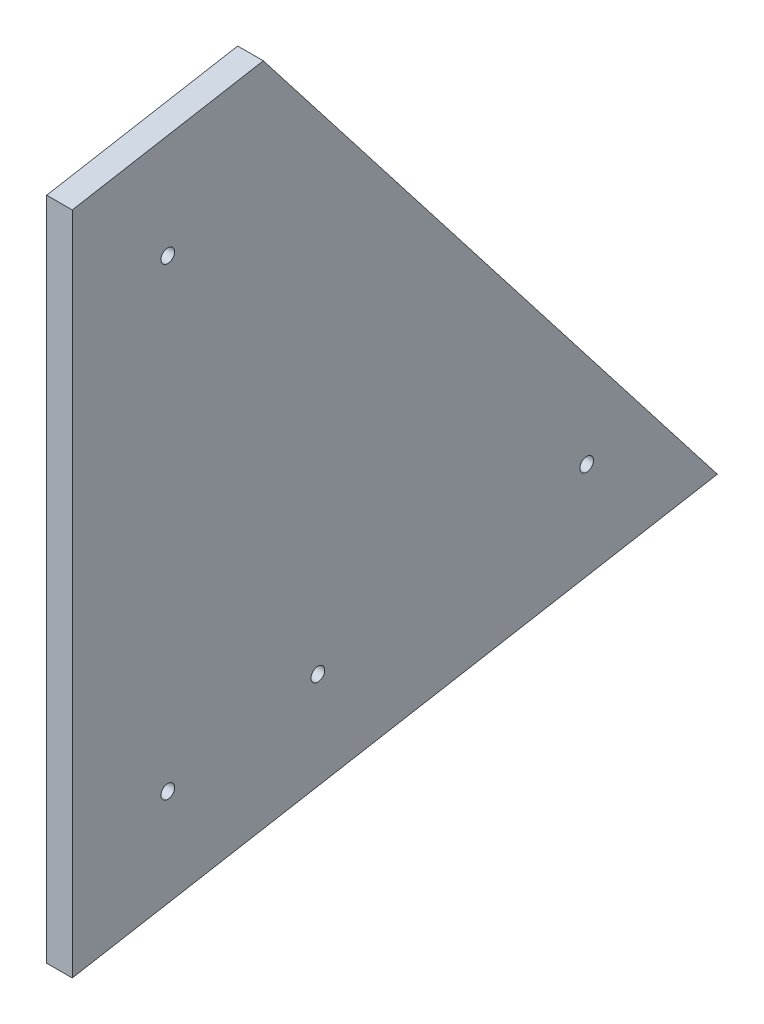
SolidWorks part; units mm, degrees
ref_plane "Front" through (0, 0, 0) normal (0, 0, 1) x (1, 0, 0)
ref_plane "Top" through (0, 0, 0) normal (0, 1, 0) x (1, 0, 0)
ref_plane "Right" through (0, 0, 0) normal (1, 0, 0) x (0, 0, -1)
sketch "Sketch1" plane through (0, 0, 0) normal (1, 0, 0) x (0, 0, -1)
  line L0 (0, 0) -> (0, 309.502)
  line L3 (0, 0) -> (300.1694, 52.928)
  line L6 (0, 309.502) -> (88.9, 325.1775)
  line L7 (88.9, 325.1775) -> (300.1694, 52.928)
  dimension "D1" = 304.8
  dimension "D2" = 80
  dimension "D3" = 100
  dimension "D4" = 304.8
  dimension "D5" = 88.9
extrude "Boss-Extrude1" add sketch "Sketch1" along normal blind 11.9062
hole_wizard "1/4 (0.25) Diameter Hole1" positions "Sketch2" profile "Sketch3" hole size "1/4" standard "ANSI Inch" end condition through all
sketch "Sketch2" plane through (11.9062, 0, 0) normal (1, 0, 0) x (0, 0, -1)
  line L0 (0, 0) -> (300.1694, 52.928) construction
  line L1 (0, 309.502) -> (0, 0) construction
  point P0 (44.45, 52.9734)
  point P3 (114.3, 65.2899)
  point P6 (239.3706, 87.3432)
  point P9 (44.45, 268.8734)
  dimension "D1" = 44.45
  dimension "D2" = 44.45
  dimension "D3" = 44.45
  dimension "D4" = 215.9
  dimension "D5" = 44.45
  dimension "D6" = 44.45
  dimension "D7" = 70.9275
  dimension "D8" = 127
sketch "Sketch3" plane through (11.9062, 52.9734, -44.45) normal (0, 1, 0) x (0, 0, -1)
  line L0 (0, 0) -> (0, 11.9062)
  line L1 (0, 11.9062) -> (3.175, 11.9062)
  line L2 (3.175, 11.9062) -> (3.175, 0)
  line L5 (3.175, 0) -> (0, 0)
  line L11 (0, -6.35) -> (0, 107.95) construction
  dimension "Thru Hole Dia." = 6.35
  dimension "Thru Hole Depth" = 11.9062
